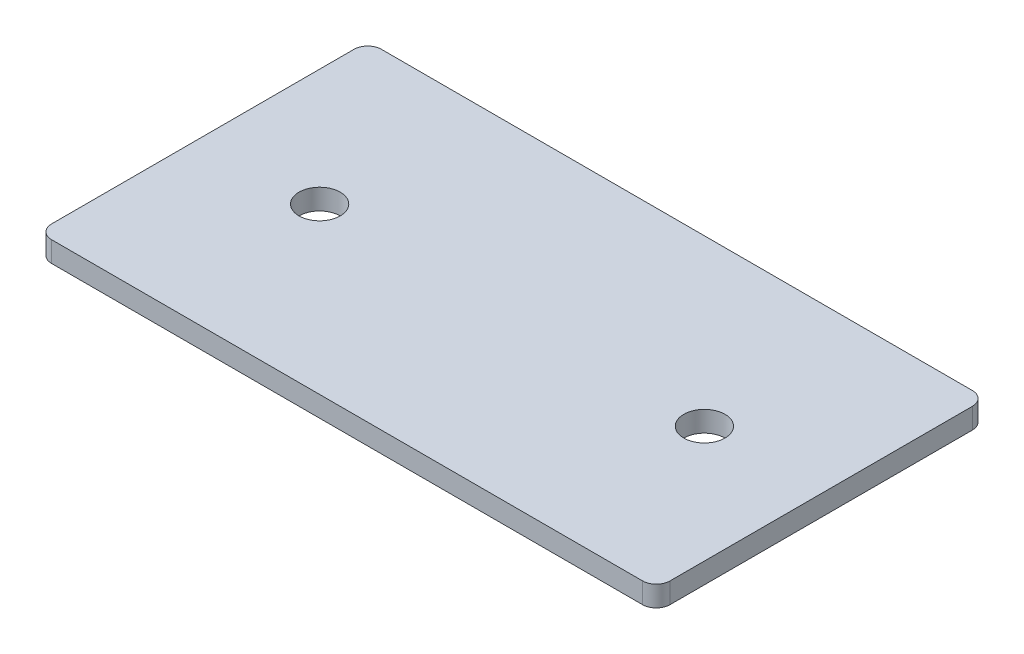
SolidWorks part; units mm, degrees
ref_plane "Front Plane" through (0, 0, 0) normal (0, 0, 1) x (1, 0, 0)
ref_plane "Top Plane" through (0, 0, 0) normal (0, 1, 0) x (1, 0, 0)
ref_plane "Right Plane" through (0, 0, 0) normal (1, 0, 0) x (0, 0, -1)
sketch "Sketch1" plane through (0, 0, 0) normal (0, 1, 0) x (1, 0, 0)
  line L1 (-22.5, -12) -> (22.5, -12)
  line L2 (-22.5, -12) -> (-22.5, 12)
  line L3 (-22.5, 12) -> (22.5, 12)
  line L4 (22.5, -12) -> (22.5, 12)
  line L5 (-22.5, -12) -> (22.5, 12) construction
  line L6 (-22.5, 12) -> (22.5, -12) construction
  point P0 (0, 0)
  dimension "D1" = 45
  dimension "D2" = 24
extrude "Boss-Extrude1" add sketch "Sketch1" along normal blind 1.5
fillet "Fillet1" radius 1 4 edges at (-22.5, 0.75, -12) (-22.5, 0.75, 12) (22.5, 0.75, -12) (22.5, 0.75, 12)
sketch "Sketch2" plane through (0, 1.5, 0) normal (0, 1, 0) x (1, 0, 0)
  line L0 (0, 0) -> (0, 50000) construction
  circle A0 centre (-14, 0) radius 1.5
  circle A1 centre (14, 0) radius 1.5
  point P5 (0, 0)
  point P7 (0, 0)
  dimension "D1" = 3
  dimension "D2" = 14
extrude "Cut-Extrude1" cut sketch "Sketch2" against normal up to next
